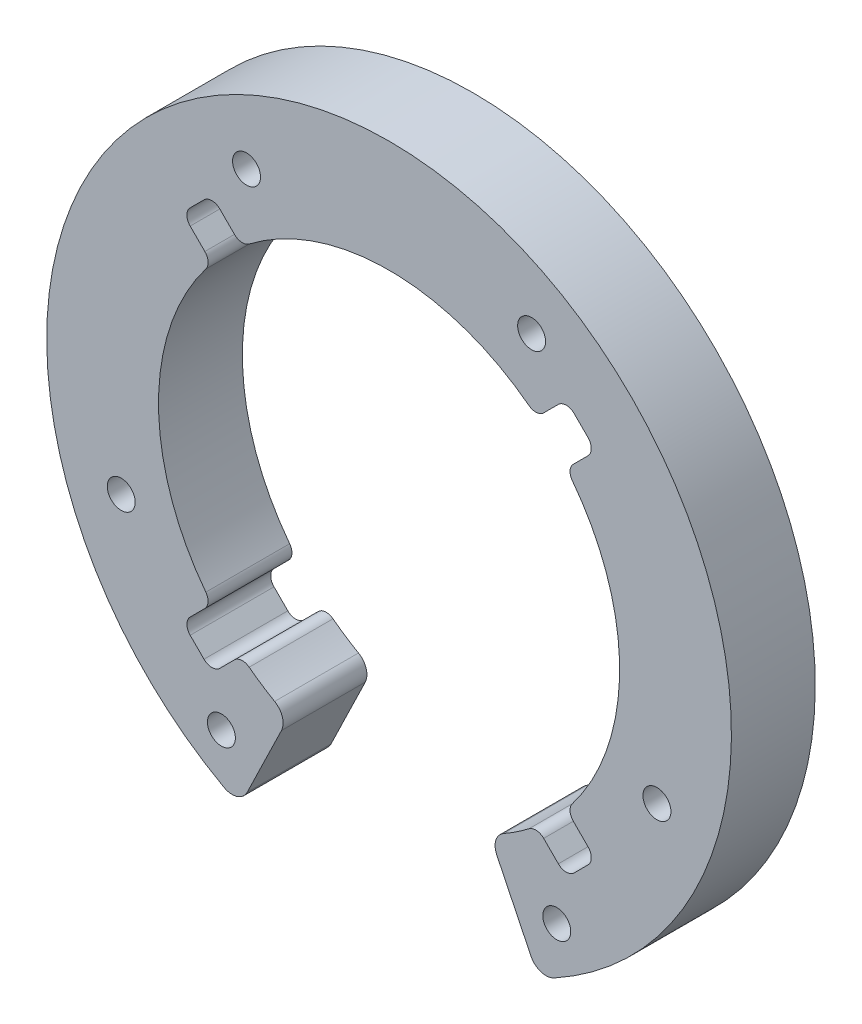
SolidWorks part; units mm, degrees
ref_plane "Plan de face" through (0, 0, 0) normal (0, 0, 1) x (1, 0, 0)
ref_plane "Plan de dessus" through (0, 0, 0) normal (0, 1, 0) x (1, 0, 0)
ref_plane "Plan de droite" through (0, 0, 0) normal (1, 0, 0) x (0, 0, -1)
sketch "Esquisse1" plane through (0, 0, 0) normal (0, 0, 1) x (1, 0, 0)
  circle A0 centre (0, 0) radius 41.25
  circle A1 centre (0, 0) radius 61.25
  dimension "D1" = 82.5
  dimension "D2" = 20
extrude "Boss.-Extru.1" add sketch "Esquisse1" along normal blind 15
sketch "Esquisse2" plane through (0, 0, 15) normal (0, 0, 1) x (1, 0, 0)
  line L0 (0, 0) -> (41.25, 0) construction
  line L1 (0, 0) -> (29.1682, 29.1682) construction
  line L2 (26.3957, 31.699) -> (31.699, 26.3957)
  line L3 (31.699, 26.3957) -> (37.0023, 31.699)
  line L4 (37.0023, 31.699) -> (31.699, 37.0023)
  line L5 (26.3957, 31.699) -> (31.699, 37.0023)
  line L6 (31.699, -26.3957) -> (26.3957, -31.699)
  line L7 (26.3957, -31.699) -> (31.699, -37.0023)
  line L8 (31.699, -37.0023) -> (37.0023, -31.699)
  line L9 (31.699, -26.3957) -> (37.0023, -31.699)
  line L10 (-26.3957, -31.699) -> (-31.699, -26.3957)
  line L11 (-31.699, -26.3957) -> (-37.0023, -31.699)
  line L12 (-37.0023, -31.699) -> (-31.699, -37.0023)
  line L13 (-26.3957, -31.699) -> (-31.699, -37.0023)
  line L14 (-31.699, 26.3957) -> (-26.3957, 31.699)
  line L15 (-26.3957, 31.699) -> (-31.699, 37.0023)
  line L16 (-31.699, 37.0023) -> (-37.0023, 31.699)
  line L17 (-31.699, 26.3957) -> (-37.0023, 31.699)
  line L18 (-29.0474, 29.0474) -> (0, 0) construction
  line L19 (-29.0474, -29.0474) -> (0, 0) construction
  line L20 (0, 0) -> (29.0474, -29.0474) construction
  circle A0 centre (0, 0) radius 41.25 construction
  point P13 (34.3507, 34.3507)
  point P14 (29.0474, 29.0474)
  point P20 (34.3507, -34.3507)
  point P21 (29.0474, -29.0474)
  point P26 (-34.3507, -34.3507)
  point P27 (-29.0474, -29.0474)
  point P32 (-34.3507, 34.3507)
  point P33 (-29.0474, 29.0474)
  dimension "D1" = 45
  dimension "D2" = 7.5
  dimension "D3" = 7.5
  dimension "D4" = 4
extrude "Enlèv. mat.-Extru.1" cut sketch "Esquisse2" against normal through all both and the other way through all
sketch "Esquisse3" plane through (0, 0, 15) normal (0, 0, 1) x (1, 0, 0)
  line L0 (0, -40.4258) -> (0, 0) construction
  line L1 (0, -61.25) -> (0, -40.4258) construction
  line L2 (-26.7273, -55.1109) -> (-18, -37.1155)
  line L3 (-18, -37.1155) -> (0, 0) construction
  line L4 (26.7273, -55.1109) -> (18, -37.1155)
  arc A0 (-18, -37.1155) -> (18, -37.1155) centre (0, 0) ccw
  arc A1 (-26.3957, -31.699) -> (26.3957, -31.699) centre (0, 0) ccw construction
  arc A2 (-26.7273, -55.1109) -> (26.7273, -55.1109) centre (0, 0) ccw
  circle A3 centre (0, 0) radius 61.25 construction
  dimension "D1" = 36
extrude "Enlèv. mat.-Extru.2" cut sketch "Esquisse3" against normal through all both and the other way through all
fillet "Congé1" radius 2 16 edges at (-31.699, 26.3957, 7.5) (-37.0023, 31.699, 7.5) (-31.699, 37.0023, 7.5) (-26.3957, 31.699, 7.5) (26.3957, 31.699, 7.5) (31.699, 37.0023, 7.5) (37.0023, 31.699, 7.5) (31.699, 26.3957, 7.5) (31.699, -26.3957, 7.5) (37.0023, -31.699, 7.5) (31.699, -37.0023, 7.5) (26.3957, -31.699, 7.5) (-26.3957, -31.699, 7.5) (-31.699, -26.3957, 7.5) (-37.0023, -31.699, 7.5) (-31.699, -37.0023, 7.5)
fillet "Congé2" radius 3 4 edges at (26.7273, -55.1109, 7.5) (18, -37.1155, 7.5) (-18, -37.1155, 7.5) (-26.7273, -55.1109, 7.5)
sketch "Esquisse4" plane through (0, 0, 15) normal (0, 0, 1) x (1, 0, 0)
  line L0 (-30, -45) -> (0, -45) construction
  line L1 (0, -45) -> (0, 0) construction
  line L2 (0, 0) -> (-47.9243, -17.443) construction
  line L3 (0, 0) -> (-57.5562, 20.9487) construction
  circle A0 centre (-30, -45) radius 2.5
  circle A1 centre (30, -45) radius 2.5
  circle A2 centre (-47.9243, -17.443) radius 2.5
  arc A3 (29.5301, -53.6613) -> (-29.5301, -53.6613) centre (0, 0) ccw construction
  circle A4 centre (-25.5, 44.1673) radius 2.5
  circle A5 centre (25.5, 44.1673) radius 2.5
  circle A6 centre (47.9243, -17.443) radius 2.5
  dimension "D3" = 5
  dimension "D5" = 5
  dimension "D1" = 45
  dimension "D2" = 30
  dimension "D4" = 51
  dimension "D6" = 70
  dimension "D7" = 40
extrude "Enlèv. mat.-Extru.3" cut sketch "Esquisse4" against normal through all both and the other way through all
